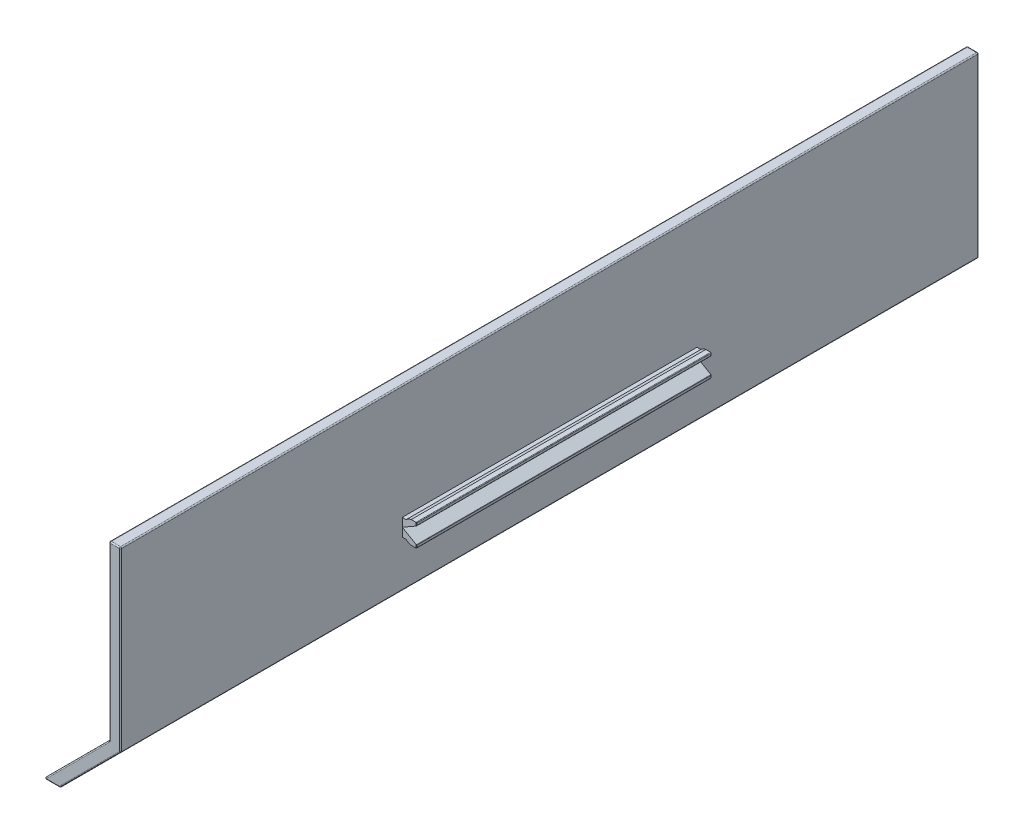
SolidWorks part; units mm, degrees
ref_plane "前视基准面" through (0, 0, 0) normal (0, 0, 1) x (1, 0, 0)
ref_plane "上视基准面" through (0, 0, 0) normal (0, 1, 0) x (1, 0, 0)
ref_plane "右视基准面" through (0, 0, 0) normal (1, 0, 0) x (0, 0, -1)
sketch "草图1" plane through (0, 0, 0) normal (0, 0, 1) x (1, 0, 0)
  line L0 (0, 0) -> (0, 31)
  line L1 (0, 0) -> (-10.6066, -10.6066)
  line L2 (-10.6066, -10.6066) -> (-13.435, -10.6066)
  line L3 (-2, 0.8284) -> (-2, 31)
  line L4 (-2, 0.8284) -> (-13.435, -10.6066)
  line L5 (-2, 31) -> (0, 31)
  line L6 (-1.4142, 1.4142) -> (-12.0208, -9.1924) construction
  line L7 (-2, 0) -> (-2, 31) construction
  dimension "D1" = 31
  dimension "D2" = 135
  dimension "D3" = 15
  dimension "D4" = 2
  dimension "D5" = 2
extrude "凸台-拉伸1" add sketch "草图1" along normal blind 150
sketch "草图3" plane through (0, 0, 150) normal (0, 0, 1) x (1, 0, 0)
  line L0 (0, 31) -> (0, 9.5) construction
  line L1 (0, 0) -> (0, 31) construction
  line L2 (0, 9.5) -> (2, 9.5) construction
  line L3 (2, 9.5) -> (2.5, 9.5) construction
  line L4 (0, 9.5) -> (0, 8)
  line L5 (0, 8) -> (0.6771, 8)
  line L6 (2.5, 8.0566) -> (2.5, 7.55)
  line L7 (2.5, 7.55) -> (1.5556, 7.55)
  line L8 (0, 9.5) -> (2.5, 8.0566)
  line L9 (2.5, 9.5) -> (2.5, 8.0566) construction
  arc A0 (0.6771, 8) -> (1.5556, 7.55) centre (2, 9.5) ccw
  dimension "D7" = 2
  dimension "D1" = 21.5
  dimension "D2" = 2
  dimension "D3" = 0.5
  dimension "D4" = 1.5
  dimension "D5" = 1.95
  dimension "D6" = 90
  dimension "D8" = 30
extrude "凸台-拉伸2" add sketch "草图3" against normal blind 51.5 from offset 49.25 offset against normal yes
ref_plane "基准面1" through (0, 9.5, 0) normal (0, 1, 0) x (1, 0, 0)
mirror "镜向1" about plane through (0, 9.5, 0) normal (0, 1, 0) of "凸台-拉伸2"
fillet "圆角1" radius 0.1 8 edges at (2.5, 8.0566, 75) (2.5, 7.8033, 49.25) (2.5, 7.55, 75) (2.5, 7.8033, 100.75) (2.5, 11.45, 75) (2.5, 11.1967, 49.25) (2.5, 10.9434, 75) (2.5, 11.1967, 100.75)
fillet "圆角2" radius 0.2 18 edges at (0, 15.5, 0) (-2, 15.9142, 0) (-7.7175, -4.8891, 0) (-5.3033, -5.3033, 0) (-13.435, -10.6066, 75) (-10.6066, -10.6066, 75) (-12.0208, -10.6066, 0) (0, 31, 75) (-2, 31, 75) (-1, 31, 0) (-12.0208, -10.6066, 150) (-7.7175, -4.8891, 150) (-2, 15.9142, 150) (-1, 31, 150) (0, 15.5, 150) (-5.3033, -5.3033, 150) (0, 0, 75) (-2, 0.8284, 75)
